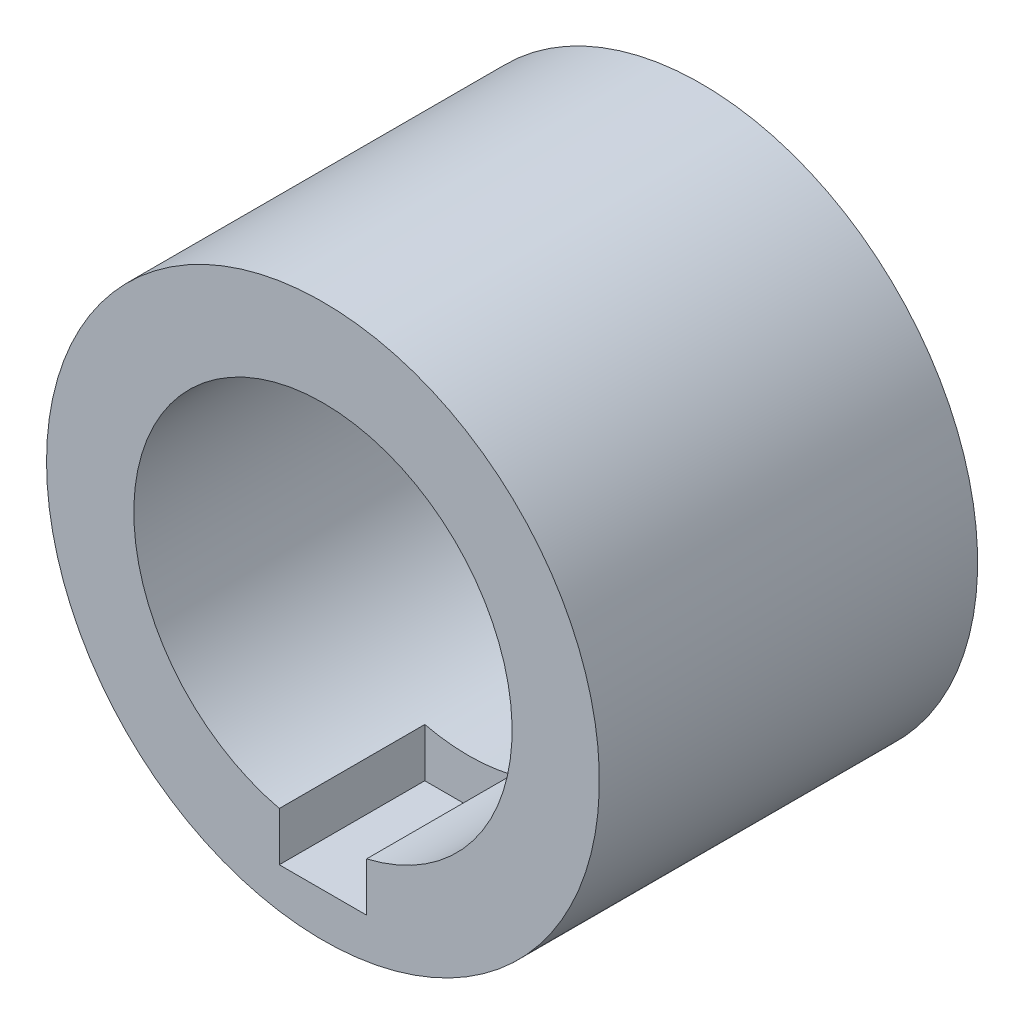
SolidWorks part; units mm, degrees
material "Plain Carbon Steel"
ref_plane "Front Plane" through (0, 0, 0) normal (0, 0, 1) x (1, 0, 0)
ref_plane "Top Plane" through (0, 0, 0) normal (0, 1, 0) x (1, 0, 0)
ref_plane "Right Plane" through (0, 0, 0) normal (1, 0, 0) x (0, 0, -1)
sketch "Sketch1" plane through (0, 0, 0) normal (0, 0, 1) x (1, 0, 0)
  circle A0 centre (0, 0) radius 6.5
  circle A1 centre (0, 0) radius 9.5
  dimension "D1" = 13
  dimension "D2" = 19
extrude "Boss-Extrude1" add sketch "Sketch1" along normal mid plane 13 contours A1 A0
sketch "Sketch2" plane through (0, 0, 0) normal (0, 1, 0) x (1, 0, 0)
  line L0 (0, 0) -> (0, -50000) construction
  line L1 (-9.5, -6.5) -> (9.5, -6.5) construction
  line L2 (-1.5, -1.5) -> (1.5, -1.5)
  line L3 (-1.5, -1.5) -> (-1.5, -6.5)
  line L4 (-1.5, -6.5) -> (1.5, -6.5)
  line L5 (1.5, -1.5) -> (1.5, -6.5)
  line L6 (-1.5, -1.5) -> (1.5, -6.5) construction
  line L7 (-1.5, -6.5) -> (1.5, -1.5) construction
  point P3 (0, -4)
  dimension "D1" = 3
  dimension "5" = 5
extrude "Cut-Extrude1" cut sketch "Sketch2" along normal up to next from offset 8 offset against normal yes
